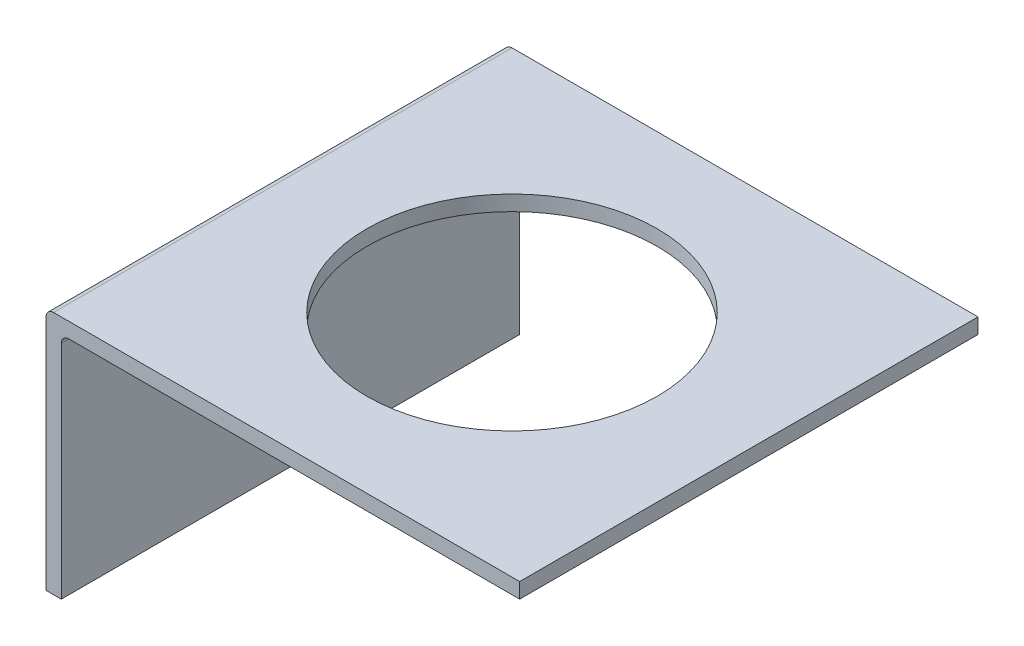
SolidWorks part; units mm, degrees
material "201 Annealed Stainless Steel (SS)"
ref_plane "Front Plane" through (0, 0, 0) normal (0, 0, 1) x (1, 0, 0)
ref_plane "Top Plane" through (0, 0, 0) normal (0, 1, 0) x (1, 0, 0)
ref_plane "Right Plane" through (0, 0, 0) normal (1, 0, 0) x (0, 0, -1)
sketch "Sketch1" plane through (0, 0, 0) normal (0, 1, 0) x (1, 0, 0)
  line L1 (-31, -30) -> (31, -30)
  line L2 (-31, -30) -> (-31, 30)
  line L3 (-31, 30) -> (31, 30)
  line L4 (31, -30) -> (31, 30)
  line L5 (-31, -30) -> (31, 30) construction
  line L6 (-31, 30) -> (31, -30) construction
  point P0 (0, 0)
  dimension "D1" = 60
  dimension "D2" = 62
extrude "Boss-Extrude1" add sketch "Sketch1" along normal blind 2
sketch "Sketch2" plane through (0, 0, 0) normal (0, -1, 0) x (1, 0, 0)
  line L1 (-29, -29.9959) -> (-31, -29.9959)
  line L2 (-29, -29.9959) -> (-29, 30)
  line L3 (-29, 30) -> (-31, 30)
  line L4 (-31, -29.9959) -> (-31, 30)
  line L5 (-29, -29.9959) -> (-31, 30) construction
  line L6 (-29, 30) -> (-31, -29.9959) construction
  point P0 (-30, 0.0021)
  dimension "D1" = 2
extrude "Boss-Extrude2" add sketch "Sketch2" along normal blind 30 contours L2 L3 L4 L1
fillet "Fillet1" radius 1 2 edges at (-31, 2, 0)
sketch "Sketch3" plane through (0, 2, 0) normal (0, 1, 0) x (1, 0, 0)
  circle A0 centre (0, 0) radius 19
  dimension "D1" = 38
extrude "Cut-Extrude1" cut sketch "Sketch3" against normal through all
